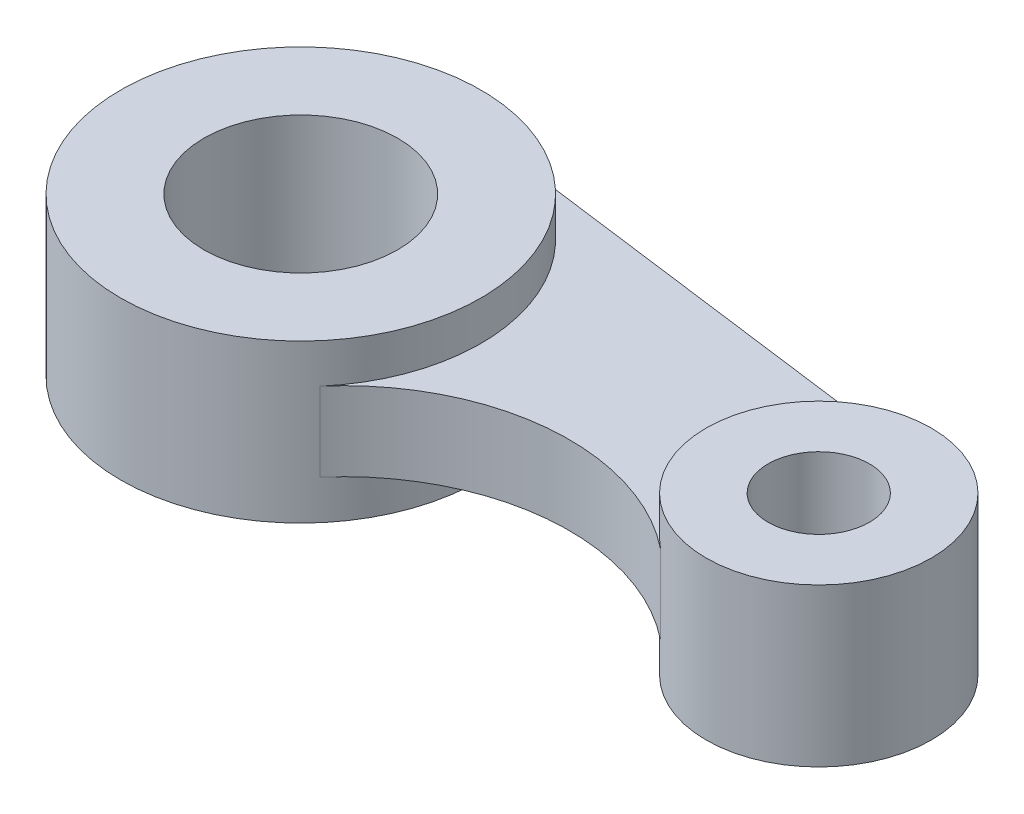
SolidWorks part; units mm, degrees
ref_plane "정면" through (0, 0, 0) normal (0, 0, 1) x (1, 0, 0)
ref_plane "윗면" through (0, 0, 0) normal (0, 1, 0) x (1, 0, 0)
ref_plane "우측면" through (0, 0, 0) normal (1, 0, 0) x (0, 0, -1)
sketch "스케치1" plane through (0, 0, 0) normal (0, 1, 0) x (1, 0, 0)
  line L0 (-112.4643, 79.3166) -> (113.6227, 49.5728)
  circle A0 centre (-122.899, 0) radius 80
  circle A1 centre (-122.899, 0) radius 43
  circle A2 centre (107.101, 0) radius 50
  circle A3 centre (107.101, 0) radius 22.5
  arc A4 (75.9415, -39.1036) -> (-62.2227, -52.1381) centre (13.6227, -117.3108) ccw
  dimension "D1" = 160
  dimension "D2" = 100
  dimension "D3" = 37
  dimension "D4" = 27.5
  dimension "D6" = 200
  dimension "D5" = 230
extrude "보스-돌출1" add sketch "스케치1" along normal blind 70 contours A0 A1 | A2 A3
sketch "스케치2" plane through (0, 70, 0) normal (0, 1, 0) x (1, 0, 0)
  line L0 (-112.4643, 79.3166) -> (113.6227, 49.5728)
  circle A0 centre (-122.899, 0) radius 80 construction
  circle A1 centre (107.101, 0) radius 50 construction
  arc A2 (75.9415, -39.1036) -> (-62.2227, -52.1381) centre (13.6227, -117.3108) ccw
  arc A3 (113.6227, 49.5728) -> (75.9415, -39.1036) centre (107.101, 0) ccw
  arc A4 (-62.2227, -52.1381) -> (-112.4643, 79.3166) centre (-122.899, 0) ccw
  dimension "D1" = 200
extrude "보스-돌출2" add sketch "스케치2" against normal blind 35 from offset 17.5 contours A2 A4 L0 A3
equation "\"17.5.00mm\"=0"
